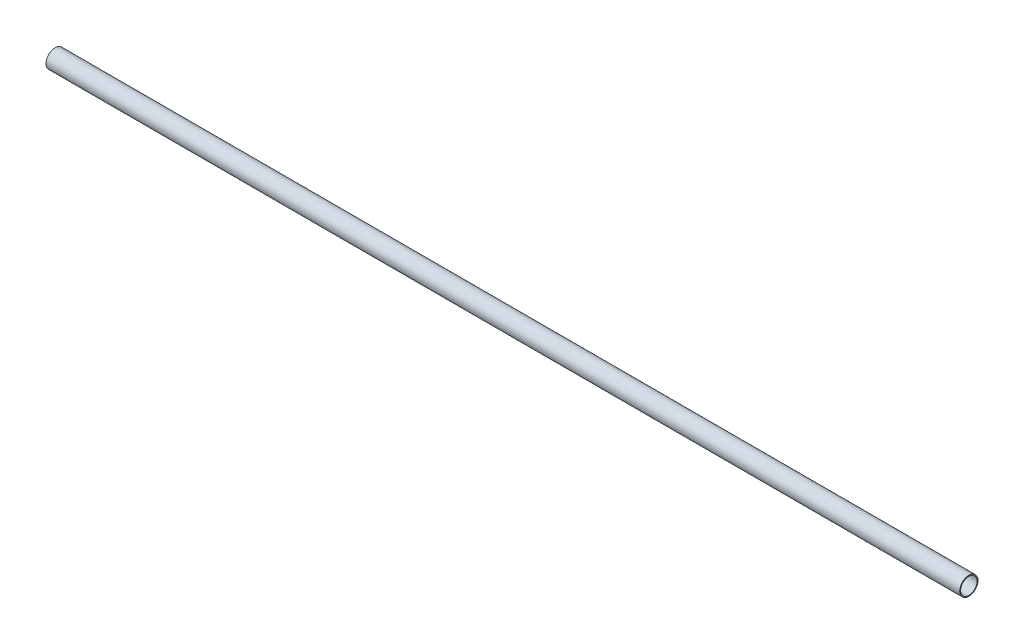
SolidWorks part; units mm, degrees
material "windcatcher"
ref_plane "Front Plane" through (0, 0, 0) normal (0, 0, 1) x (1, 0, 0)
ref_plane "Top Plane" through (0, 0, 0) normal (0, 1, 0) x (1, 0, 0)
ref_plane "Right Plane" through (0, 0, 0) normal (1, 0, 0) x (0, 0, -1)
sketch "Sketch1" plane through (0, 0, 0) normal (1, 0, 0) x (0, 0, -1)
  circle A0 centre (0, 0) radius 10
  circle A1 centre (0, 0) radius 9
  dimension "D1" = 20
  dimension "D2" = 18
extrude "Boss-Extrude1" add sketch "Sketch1" along normal mid plane 1000
